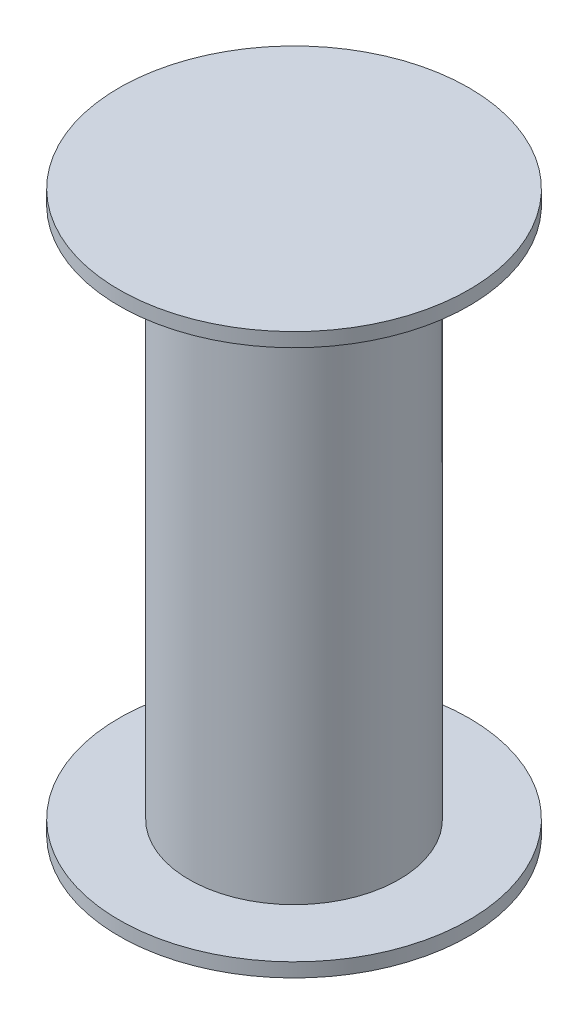
SolidWorks part; units mm, degrees
material "Plastique personnalisé"
ref_plane "Plan de face" through (0, 0, 0) normal (0, 0, 1) x (1, 0, 0)
ref_plane "Plan de dessus" through (0, 0, 0) normal (0, 1, 0) x (1, 0, 0)
ref_plane "Plan de droite" through (0, 0, 0) normal (1, 0, 0) x (0, 0, -1)
sketch "Esquisse1" plane through (0, 0, 0) normal (0, 0, 1) x (1, 0, 0)
  line L0 (0, -6.9457) -> (0, -11.5761)
  line L1 (-7.5, 31.0543) -> (-7.5, -6.9457)
  line L2 (-12.5, -7.9457) -> (12.5, -7.9457)
  line L3 (-12.5, -7.9457) -> (-12.5, -6.9457)
  line L4 (-12.5, -6.9457) -> (-7.5, -6.9457)
  line L5 (12.5, -7.9457) -> (12.5, -6.9457)
  line L6 (-12.5, -7.9457) -> (12.5, -6.9457) construction
  line L7 (-12.5, -6.9457) -> (12.5, -7.9457) construction
  line L9 (0, -6.9457) -> (7.5, -6.9457)
  line L10 (7.5, 31.0543) -> (7.5, -6.9457)
  line L11 (0, 12.0543) -> (0, -27.0147)
  line L12 (0, -27.0147) -> (0, 44.1726)
  line L15 (12.5, 32.0543) -> (12.5, 31.0543)
  line L16 (-12.5, 31.0543) -> (-7.5, 31.0543)
  line L17 (-12.5, 32.0543) -> (12.5, 32.0543)
  line L18 (-12.5, 32.0543) -> (-12.5, 31.0543)
  line L19 (7.5, 31.0543) -> (12.5, 31.0543)
  line L21 (0, -6.9457) -> (12.5, -6.9457)
  point P3 (0, -7.4457)
  point P9 (0, 12.0543)
  dimension "D1" = 1
  dimension "D2" = 25
  dimension "D3" = 38
  dimension "D4" = 15
revolve "Révolution1" add sketch "Esquisse1" angle 360 about L12
